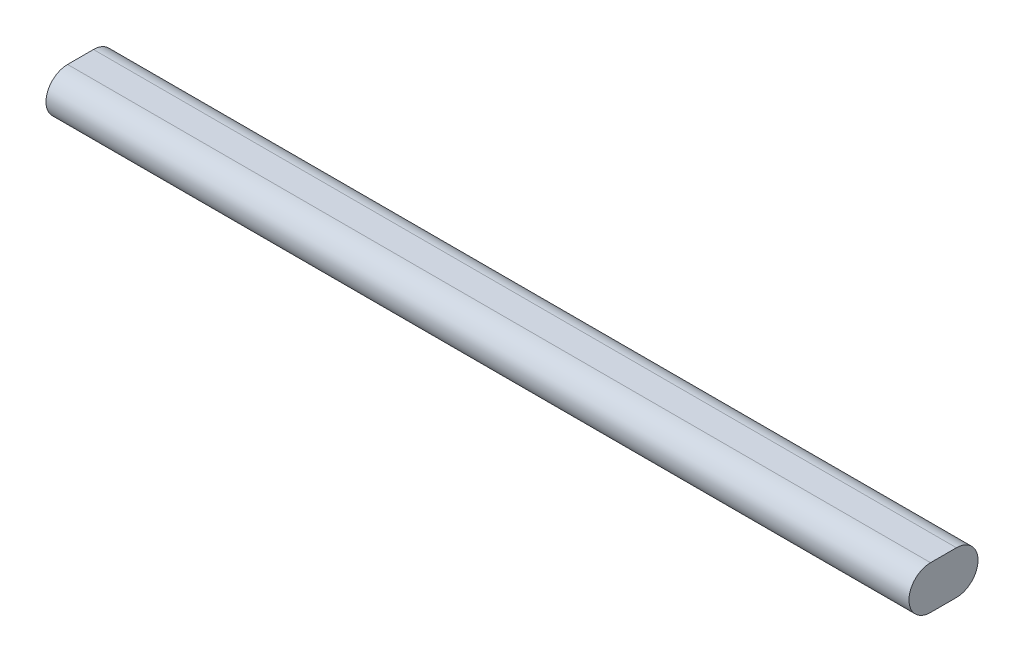
SolidWorks part; units mm, degrees
material "Balsa"
ref_plane "Alzado" through (0, 0, 0) normal (0, 0, 1) x (1, 0, 0)
ref_plane "Planta" through (0, 0, 0) normal (0, 1, 0) x (1, 0, 0)
ref_plane "Vista lateral" through (0, 0, 0) normal (1, 0, 0) x (0, 0, -1)
sketch "Croquis1" plane through (0, 0, 0) normal (1, 0, 0) x (0, 0, -1)
  line L0 (-12.5, 0) -> (27.5, 0) construction
  line L1 (0, 12.5) -> (15, 12.5)
  line L2 (0, -12.5) -> (15, -12.5)
  arc A0 (0, 12.5) -> (0, -12.5) centre (0, 0) ccw
  arc A1 (15, -12.5) -> (15, 12.5) centre (15, 0) ccw
  point P11 (0, 0)
  point P12 (0, 0)
  dimension "D1" = 25
  dimension "D2" = 25
  dimension "D3" = 40
extrude "Saliente-Extruir1" add sketch "Croquis1" along normal blind 500
